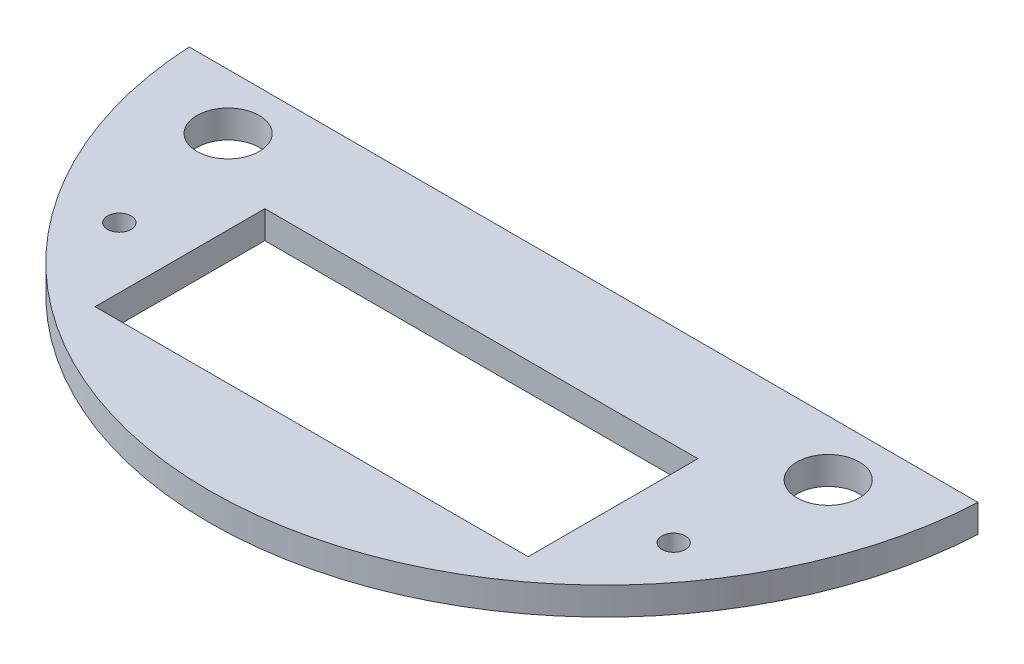
SolidWorks part; units mm, degrees
ref_plane "Plan de face" through (0, 0, 0) normal (0, 0, 1) x (1, 0, 0)
ref_plane "Plan de dessus" through (0, 0, 0) normal (0, 1, 0) x (1, 0, 0)
ref_plane "Plan de droite" through (0, 0, 0) normal (1, 0, 0) x (0, 0, -1)
sketch "Esquisse1" plane through (0, 0, 0) normal (0, 1, 0) x (1, 0, 0)
  line L0 (-58.9016, -13.5321) -> (-58.9016, 27)
  line L1 (31.25, 12.25) -> (-31.25, 12.25)
  line L2 (31.25, 12.25) -> (31.25, -12.25)
  line L3 (31.25, -12.25) -> (-31.25, -12.25)
  line L4 (-31.25, 12.25) -> (-31.25, -12.25)
  line L5 (31.25, 12.25) -> (-31.25, -12.25) construction
  line L6 (31.25, -12.25) -> (-31.25, 12.25) construction
  line L7 (-58.9016, 27) -> (59.4279, 27)
  line L8 (59.4279, 27) -> (59.4279, -12.7564)
  line L9 (0, 0) -> (0, 27) construction
  line L10 (-58.9016, -13.5321) -> (0, 27) construction
  line L11 (0, 27) -> (59.4279, -12.7564) construction
  line L12 (-43.3, 1.9978) -> (43.3, 1.9978) construction
  line L13 (43.3, 1.9978) -> (0, 27) construction
  line L14 (0, 27) -> (-43.3, 1.9978) construction
  line L15 (-58.9016, -13.5321) -> (-58.9016, -41.6944)
  line L16 (-58.9016, -41.6944) -> (59.4279, -41.6944)
  line L17 (59.4279, -41.6944) -> (59.4279, -12.7564)
  circle A0 centre (0, 27) radius 57 construction
  point P8 (43.3, 1.9978)
  point P13 (0, 27)
  point P14 (-43.3, 1.9978)
  point P16 (0, 1.9978)
  dimension "D3" = 71.5
  dimension "D6" = 114
  dimension "D1" = 24.5
  dimension "D2" = 62.5
  dimension "D4" = 50
  dimension "D5" = 86.6
  dimension "D7" = 27
  dimension "D8" = 0
extrude "Boss.-Extru.1" add sketch "Esquisse1" along normal blind 4
hole_wizard "Dégagement M81" positions "Esquisse2" profile "Esquisse4" hole size "M8" standard "DIN" end condition through all
sketch "Esquisse2" plane through (0, 4, 0) normal (0, 1, 0) x (1, 0, 0)
  line L0 (-43.3, 19) -> (0, 0) construction
  line L1 (0, 0) -> (43.3, 19) construction
  line L2 (43.3, 19) -> (-43.3, 19) construction
  point P0 (-43.3, 19)
  point P2 (43.3, 19)
  point P12 (-43.3, 18.8974)
  dimension "D1" = 86.6
  dimension "D2" = 19
sketch "Esquisse4" plane through (-43.3, 4, -19) normal (1, 0, 0) x (0, 0, 1)
  line L0 (0, 0) -> (0, 4)
  line L1 (0, 4) -> (4.5, 4)
  line L2 (4.5, 4) -> (4.5, 0)
  line L5 (4.5, 0) -> (0, 0)
  line L11 (0, -6.35) -> (0, 107.95) construction
  dimension "Diamètre du perçage jusqu'au prochain" = 9
  dimension "Profondeur du perçage jusqu'au prochain" = 4
sketch "Esquisse5" plane through (0, 4, 0) normal (0, 1, 0) x (1, 0, 0)
  line L0 (0, 30) -> (0, 0) construction
  circle A0 centre (0, 30) radius 57
  circle A1 centre (0, 30) radius 132
  point P6 (-43.3, 19)
  point P8 (0, 44.0022)
  dimension "D1" = 75
  dimension "D3" = 114
  dimension "D2" = 30
extrude "Enlèv. mat.-Extru.1" cut sketch "Esquisse5" against normal through all
hole_wizard "Dégagement M31" positions "Esquisse7" profile "Esquisse8" hole size "M3" standard "DIN" end condition through all
sketch "Esquisse7" plane through (0, 0, 0) normal (0, -1, 0) x (-1, 0, 0)
  line L0 (-40, 0) -> (40, 0) construction
  circle A0 centre (-40, 0) radius 5 construction
  circle A1 centre (40, 0) radius 5 construction
  point P0 (-40, 0)
  point P2 (40, 0)
  dimension "D2" = 10
  dimension "D1" = 80
sketch "Esquisse8" plane through (40, 0, 0) normal (1, 0, 0) x (0, 0, -1)
  line L0 (0, 0) -> (0, 4)
  line L1 (0, 4) -> (1.7, 4)
  line L2 (1.7, 4) -> (1.7, 0)
  line L5 (1.7, 0) -> (0, 0)
  line L11 (0, -6.35) -> (0, 107.95) construction
  dimension "Diamètre du perçage jusqu'au prochain" = 3.4
  dimension "Profondeur du perçage jusqu'au prochain" = 4
